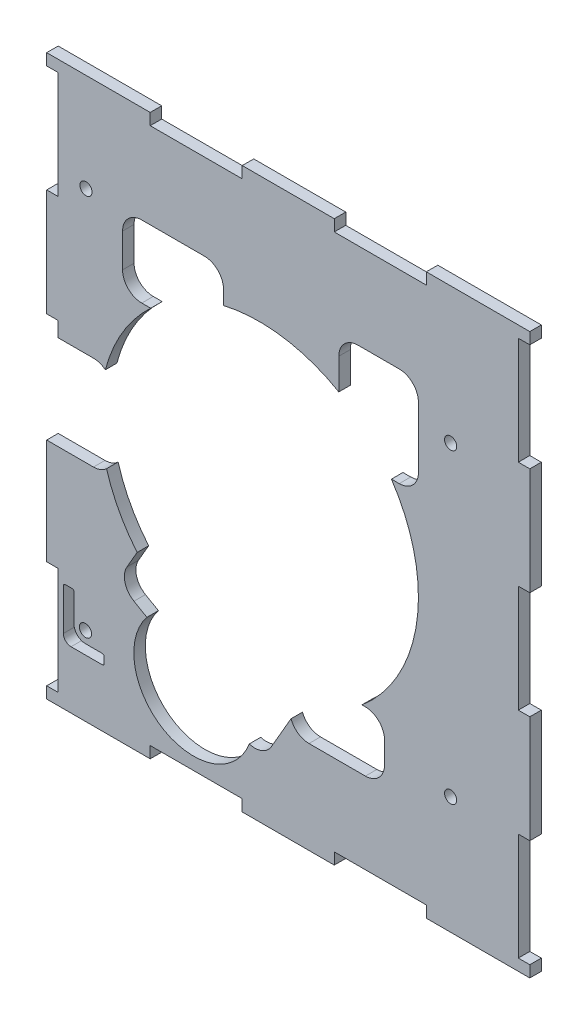
SolidWorks part; units mm, degrees
ref_plane "Front Plane" through (0, 0, 0) normal (0, 0, 1) x (1, 0, 0)
ref_plane "Top Plane" through (0, 0, 0) normal (0, 1, 0) x (1, 0, 0)
ref_plane "Right Plane" through (0, 0, 0) normal (1, 0, 0) x (0, 0, -1)
sketch "Sketch1" plane through (0, 0, 0) normal (0, 0, 1) x (1, 0, 0)
  line L1 (24, 140) -> (48, 140)
  line L2 (0, 140) -> (0, 112)
  line L3 (24, 0) -> (48, 0)
  line L4 (120, 140) -> (120, 112)
  line L5 (-3, 28) -> (-3, 56)
  line L6 (-3, 56) -> (0, 56)
  line L7 (120, 28) -> (123, 28)
  line L8 (123, 28) -> (123, 56)
  line L9 (123, 56) -> (120, 56)
  line L10 (123, 112) -> (120, 112)
  line L11 (123, 84) -> (123, 112)
  line L12 (120, 84) -> (123, 84)
  line L13 (123, 112) -> (120, 112)
  line L14 (123, 84) -> (123, 112)
  line L15 (120, 84) -> (123, 84)
  line L16 (-3, 112) -> (0, 112)
  line L17 (-3, 84) -> (-3, 112)
  line L18 (0, 84) -> (-3, 84)
  line L19 (72, 140) -> (96, 140)
  line L20 (0, 143) -> (24, 143)
  line L21 (24, 143) -> (24, 140)
  line L22 (48, 140) -> (48, 143)
  line L23 (48, 143) -> (72, 143)
  line L24 (72, 143) -> (72, 140)
  line L25 (96, 140) -> (96, 143)
  line L26 (96, 143) -> (120, 143)
  line L28 (120, 84) -> (120, 56)
  line L29 (0, -3) -> (24, -3)
  line L30 (24, -3) -> (24, 0)
  line L31 (48, 0) -> (48, -3)
  line L32 (48, -3) -> (72, -3)
  line L33 (72, -3) -> (72, 0)
  line L34 (96, 0) -> (96, -3)
  line L35 (96, -3) -> (120, -3)
  line L37 (0, 143) -> (-3, 143)
  line L38 (-3, 143) -> (-3, 140)
  line L39 (-3, 140) -> (0, 140)
  line L40 (120, 143) -> (123, 143)
  line L41 (123, 143) -> (123, 140)
  line L42 (123, 140) -> (120, 140)
  line L43 (120, -3) -> (123, -3)
  line L44 (123, -3) -> (123, 0)
  line L45 (123, 0) -> (120, 0)
  line L46 (0, 0) -> (-3, 0)
  line L47 (-3, 0) -> (-3, -3)
  line L48 (-3, -3) -> (0, -3)
  line L49 (0, 84) -> (0, 56)
  line L50 (0, 28) -> (0, 0)
  line L51 (120, -3) -> (120, 0) [skipped]
  line L52 (120, 28) -> (120, 0)
  line L53 (72, 0) -> (96, 0)
  line L54 (120, 143) -> (120, 140) [skipped]
  line L55 (84.2903, 91.6321) -> (32.35, 91.6321) construction
  line L56 (88.9468, 117.5239) -> (78.1831, 117.5239)
  line L57 (93.9468, 112.5239) -> (93.9468, 96.6321)
  line L58 (88.9468, 91.6321) -> (78.1831, 91.6321)
  line L59 (73.1831, 112.5239) -> (73.1831, 96.6321)
  line L60 (11.993, 14.0598) -> (11.993, 12.4987)
  line L61 (38.1174, 117.6046) -> (21.7939, 117.6046)
  line L62 (43.1174, 112.6046) -> (43.1174, 98.8357)
  line L63 (43.1174, 98.8357) -> (21.7939, 98.8357)
  line L64 (16.7939, 112.6046) -> (16.7939, 103.8357)
  line L65 (9.2048, 80.0916) -> (-17.6355, 80.0916)
  line L66 (14.2048, 75.0916) -> (14.2048, 60.5045)
  line L67 (9.2048, 55.5045) -> (-17.6355, 55.5045)
  line L68 (-17.6355, 80.0916) -> (-17.6355, 55.5045)
  line L69 (80.1147, 36.7967) -> (60.4079, 36.7967)
  line L70 (85.1147, 31.7967) -> (85.1147, 26.1659)
  line L71 (80.1147, 21.1659) -> (65.4079, 21.1659)
  line L72 (60.4079, 36.7967) -> (60.4079, 26.1659)
  line L77 (48.7791, 13.7325) -> (19.7641, 30.4843)
  line L78 (55.6092, 15.5626) -> (65.2588, 32.2762)
  line L79 (65.2588, 32.2762) -> (27.5835, 54.028)
  line L80 (17.9339, 37.3144) -> (27.5835, 54.028)
  line L82 (4.1115, 24.786) -> (4.1115, 17.5598)
  line L84 (1.355, 24.7912) -> (1.355, 13.9987)
  line L85 (11.493, 14.5598) -> (7.1115, 14.5598)
  line L87 (11.493, 11.9987) -> (3.355, 11.9987)
  line L88 (1.355, 15.0997) -> (1.355, 13.9987)
  line L89 (3.613, 25.286) -> (1.8565, 25.2912)
  line L90 (-3, 140) -> (0, 140)
  line L91 (-3, 28) -> (0, 28)
  circle A0 centre (52.45, 68.5103) radius 41.5
  circle A1 centre (35.281, 18.8125) radius 15.5593
  arc A2 (93.9468, 112.5239) -> (88.9468, 117.5239) centre (88.9468, 112.5239) ccw
  arc A3 (88.9468, 91.6321) -> (93.9468, 96.6321) centre (88.9468, 96.6321) ccw
  arc A4 (73.1831, 96.6321) -> (78.1831, 91.6321) centre (78.1831, 96.6321) ccw
  arc A5 (73.1831, 112.5239) -> (78.1831, 117.5239) centre (78.1831, 112.5239) cw
  arc A6 (38.1174, 117.6046) -> (43.1174, 112.6046) centre (38.1174, 112.6046) cw
  arc A7 (16.7939, 112.6046) -> (21.7939, 117.6046) centre (21.7939, 112.6046) cw
  arc A8 (21.7939, 98.8357) -> (16.7939, 103.8357) centre (21.7939, 103.8357) cw
  arc A9 (9.2048, 80.0916) -> (14.2048, 75.0916) centre (9.2048, 75.0916) cw
  arc A10 (9.2048, 55.5045) -> (14.2048, 60.5045) centre (9.2048, 60.5045) ccw
  arc A11 (19.7641, 30.4843) -> (17.9339, 37.3144) centre (22.2641, 34.8144) cw
  arc A12 (55.6092, 15.5626) -> (48.7791, 13.7325) centre (51.2791, 18.0626) cw
  arc A13 (65.4079, 21.1659) -> (60.4079, 26.1659) centre (65.4079, 26.1659) cw
  arc A14 (85.1147, 26.1659) -> (80.1147, 21.1659) centre (80.1147, 26.1659) cw
  arc A15 (80.1147, 36.7967) -> (85.1147, 31.7967) centre (80.1147, 31.7967) cw
  arc A20 (1.355, 13.9987) -> (3.355, 11.9987) centre (3.355, 13.9987) ccw
  arc A21 (11.993, 14.0598) -> (11.493, 14.5598) centre (11.493, 14.0598) ccw
  arc A22 (11.493, 11.9987) -> (11.993, 12.4987) centre (11.493, 12.4987) ccw
  arc A23 (3.613, 25.286) -> (4.1115, 24.786) centre (3.6115, 24.786) cw
  arc A24 (1.355, 24.7912) -> (1.8565, 25.2912) centre (1.855, 24.7912) cw
  arc A25 (7.1115, 14.5598) -> (4.1115, 17.5598) centre (7.1115, 17.5598) cw
  circle A26 centre (102.35, 107.5) radius 1.5875
  circle A27 centre (7.25, 117.4) radius 1.5875
  circle A28 centre (7.1115, 17.5598) radius 1.5875
  circle A29 centre (102.35, 27.6) radius 1.5875
  point P88 (73.1831, 91.6321)
  dimension "D12" = 83
  dimension "D14" = 5
  dimension "D16" = 5
  dimension "D17" = 5
  dimension "D21" = 5
  dimension "D22" = 5
  dimension "D23" = 5
  dimension "D24" = 5
  dimension "D25" = 5
  dimension "D26" = 5
  dimension "D27" = 5
  dimension "D28" = 5
  dimension "D29" = 5
  dimension "D30" = 5
  dimension "D31" = 5
  dimension "D32" = 0.5
  dimension "D33" = 0.5
  dimension "D34" = 0.5
  dimension "D35" = 3
  dimension "D36" = 2
  dimension "D5" = 0.5
  dimension "D37" = 3.175
  dimension "D38" = 3.175
  dimension "D39" = 3.175
  dimension "D40" = 3.175
  dimension "D1" = 120
  dimension "D2" = 140
  dimension "D3" = 3
  dimension "D4" = 28
  dimension "D6" = 28
  dimension "D7" = 3
  dimension "D8" = 28
  dimension "D11" = 24
  dimension "D15" = 24
  dimension "D19" = 3
  dimension "D20" = 3
  dimension "D9" = 2
  dimension "D10" = 2
  dimension "D13" = 3
  dimension "D18" = 3
extrude "Boss-Extrude1" add sketch "Sketch1" along normal blind 3
